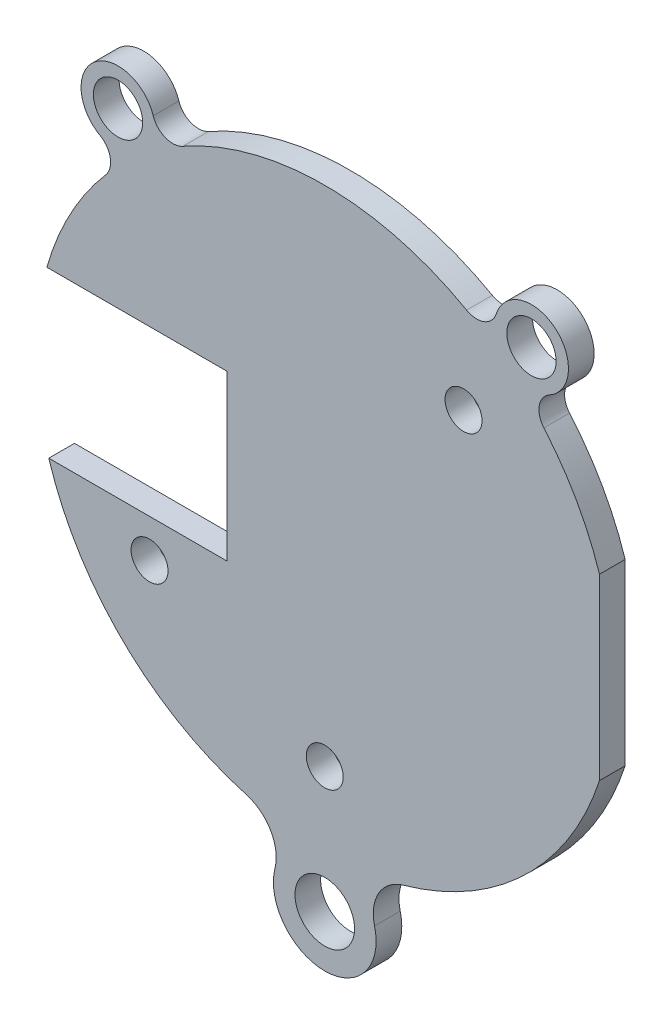
SolidWorks part; units mm, degrees
ref_plane "Front Plane" through (0, 0, 0) normal (0, 0, 1) x (1, 0, 0)
ref_plane "Top Plane" through (0, 0, 0) normal (0, 1, 0) x (1, 0, 0)
ref_plane "Right Plane" through (0, 0, 0) normal (1, 0, 0) x (0, 0, -1)
sketch "Sketch1" plane through (0, 0, 0) normal (0, 0, 1) x (1, 0, 0)
  line L0 (-6.0563, 4.8768) -> (-17.1812, 4.8768) construction
  line L2 (-17.0607, -5.2832) -> (-6.0563, -5.2832) construction
  line L5 (16.9841, -5.5245) -> (16.9841, 5.5245) construction
  line L10 (-6.0563, 4.8768) -> (-17.1812, 4.8768)
  line L11 (-6.0563, 4.8768) -> (-6.0563, -5.2832)
  line L12 (-17.0607, -5.2832) -> (-6.0563, -5.2832)
  line L15 (16.9841, -5.5245) -> (16.9841, 5.5245)
  arc A0 (-17.0607, -5.2832) -> (-4.8506, -17.1887) centre (0, 0) ccw construction
  arc A3 (4.8506, -17.1887) -> (16.9841, -5.5245) centre (0, 0) ccw construction
  arc A4 (16.9841, 5.5245) -> (13.5462, 11.6395) centre (0, 0) ccw construction
  arc A8 (-13.5462, 11.6395) -> (-17.1812, 4.8768) centre (0, 0) ccw construction
  arc A9 (-17.0607, -5.2832) -> (-4.8506, -17.1887) centre (0, 0) ccw
  arc A10 (4.8506, -17.1887) -> (3.078, -20.2562) centre (5.5404, -19.6332) ccw construction
  arc A11 (-3.078, -20.2562) -> (3.078, -20.2562) centre (0, -21.035) ccw construction
  arc A12 (4.8506, -17.1887) -> (16.9841, -5.5245) centre (0, 0) ccw
  arc A13 (16.9841, 5.5245) -> (13.5462, 11.6395) centre (0, 0) ccw
  arc A14 (-3.078, -20.2562) -> (-4.8506, -17.1887) centre (-5.5404, -19.6332) ccw construction
  arc A15 (8.7709, 15.5579) -> (-8.7709, 15.5579) centre (0, 0) ccw
  arc A16 (-13.5462, 11.6395) -> (-13.8916, 13.5768) centre (-14.5094, 12.4672) ccw construction
  arc A17 (-13.5462, 11.6395) -> (-17.1812, 4.8768) centre (0, 0) ccw
  arc A20 (-10.6034, 16.2749) -> (-13.8916, 13.5768) centre (-12.7793, 15.574) ccw construction
  arc A21 (-10.6034, 16.2749) -> (-8.7709, 15.5579) centre (-9.3946, 16.6642) ccw construction
  arc A22 (8.7709, 15.5579) -> (10.6034, 16.2749) centre (9.3946, 16.6642) ccw construction
  arc A23 (13.8916, 13.5768) -> (10.6034, 16.2749) centre (12.7793, 15.574) ccw construction
  arc A24 (13.8916, 13.5768) -> (13.5462, 11.6395) centre (14.5094, 12.4672) ccw construction
  arc A25 (4.8506, -17.1887) -> (3.078, -20.2562) centre (5.5404, -19.6332) ccw
  arc A26 (-3.078, -20.2562) -> (3.078, -20.2562) centre (0, -21.035) ccw
  arc A27 (-3.078, -20.2562) -> (-4.8506, -17.1887) centre (-5.5404, -19.6332) ccw
  arc A28 (-13.5462, 11.6395) -> (-13.8916, 13.5768) centre (-14.5094, 12.4672) ccw
  arc A29 (-10.6034, 16.2749) -> (-13.8916, 13.5768) centre (-12.7793, 15.574) ccw
  arc A30 (-10.6034, 16.2749) -> (-8.7709, 15.5579) centre (-9.3946, 16.6642) ccw
  arc A31 (8.7709, 15.5579) -> (10.6034, 16.2749) centre (9.3946, 16.6642) ccw
  arc A32 (13.8916, 13.5768) -> (10.6034, 16.2749) centre (12.7793, 15.574) ccw
  arc A33 (13.8916, 13.5768) -> (13.5462, 11.6395) centre (14.5094, 12.4672) ccw
  circle A34 centre (0, -21.035) radius 1.8415 construction
  circle A35 centre (12.7793, 15.574) radius 1.524 construction
  circle A36 centre (-12.7793, 15.574) radius 1.524 construction
  circle A37 centre (0, -21.035) radius 1.8415
  circle A38 centre (12.7793, 15.574) radius 1.524
  circle A39 centre (-12.7793, 15.574) radius 1.524
extrude "Boss-Extrude1" add sketch "Sketch1" along normal blind 1.5875
sketch "Sketch2" plane through (0, 0, 1.5875) normal (0, 0, 1) x (1, 0, 0)
  circle A0 centre (8.579, 10.1092) radius 1.143
  circle A1 centre (-10.8325, -7.6454) radius 1.143
  circle A2 centre (0, -13.2588) radius 1.143
  circle A3 centre (-10.8325, -7.6454) radius 1.143 construction
  circle A4 centre (0, -13.2588) radius 1.143 construction
  circle A5 centre (8.579, 10.1092) radius 1.143 construction
extrude "Cut-Extrude1" cut sketch "Sketch2" against normal through all
